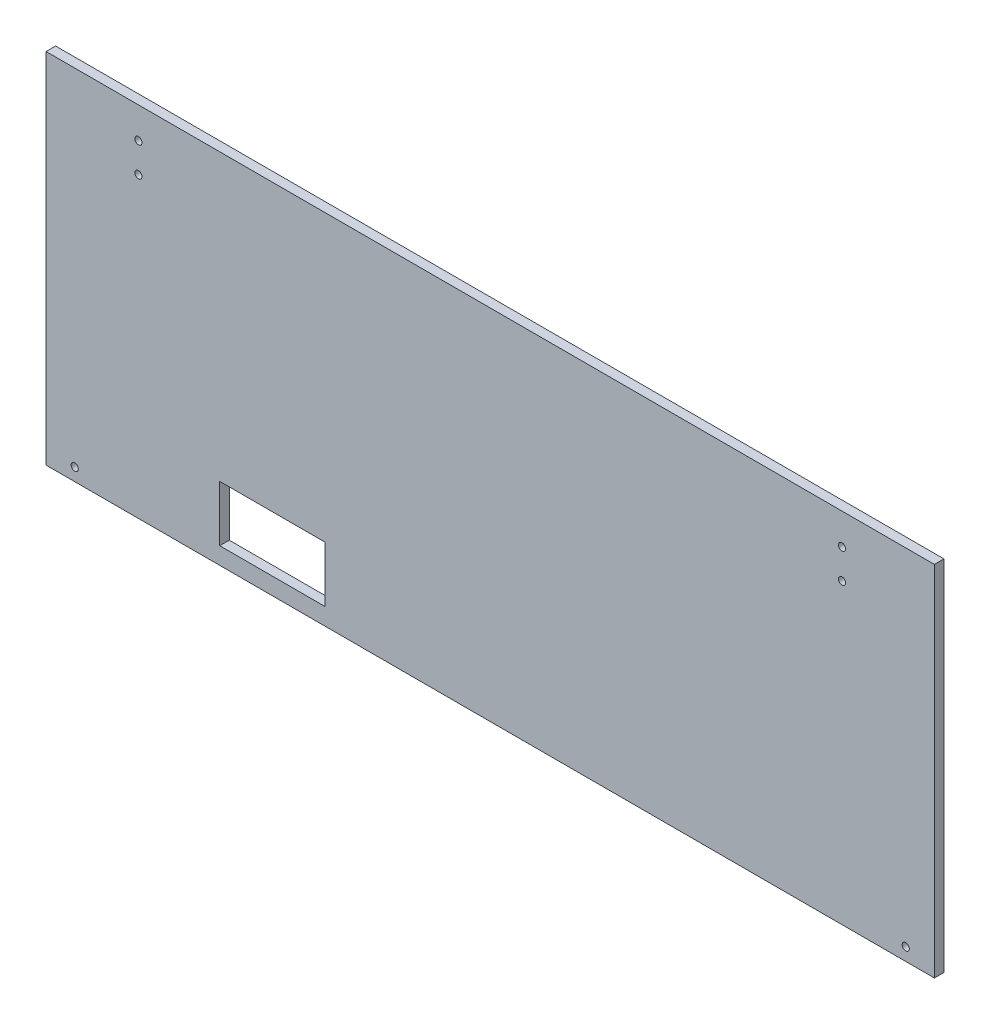
SolidWorks part; units mm, degrees
material "Pino"
ref_plane "Piano frontale" through (0, 0, 0) normal (0, 0, 1) x (1, 0, 0)
ref_plane "Piano superiore" through (0, 0, 0) normal (0, 1, 0) x (1, 0, 0)
ref_plane "Piano destro" through (0, 0, 0) normal (1, 0, 0) x (0, 0, -1)
sketch "Schizzo1" plane through (0, 0, 0) normal (0, 0, 1) x (1, 0, 0)
  line L1 (279, -112.5) -> (-279, -112.5)
  line L2 (279, -112.5) -> (279, 112.5)
  line L3 (279, 112.5) -> (-279, 112.5)
  line L4 (-279, -112.5) -> (-279, 112.5)
  line L5 (279, -112.5) -> (-279, 112.5) construction
  line L6 (279, 112.5) -> (-279, -112.5) construction
  point P4 (0, 0)
  dimension "D1" = 225
  dimension "D2" = 558
extrude "Estrusione-Estrusione1" add sketch "Schizzo1" along normal blind 6
sketch "Schizzo2" plane through (0, 0, 0) normal (0, 0, -1) x (-1, 0, 0)
  line L0 (279, -112.5) -> (-279, -112.5) construction
  line L1 (103.9257, -101.8) -> (169.9257, -101.8)
  line L2 (103.9257, -101.8) -> (103.9257, -66.8)
  line L3 (103.9257, -66.8) -> (169.9257, -66.8)
  line L4 (169.9257, -101.8) -> (169.9257, -66.8)
  line L5 (279, 112.5) -> (279, -112.5) construction
  line L6 (-279, -112.5) -> (-279, 112.5) construction
  circle A0 centre (-221, 93) radius 2.25
  circle A1 centre (-221, 74.5) radius 2.25
  circle A2 centre (221, 93) radius 2.25
  circle A3 centre (221, 74.5) radius 2.25
  circle A4 centre (-261, -104.5) radius 2.25
  circle A5 centre (261, -104.5) radius 2.25
  point P28 (-252.9189, -112.2718)
  dimension "D1" = 4.5
  dimension "D2" = 10.7
  dimension "D3" = 66
  dimension "D4" = 109.0743
  dimension "D5" = 35
  dimension "D6" = 18
  dimension "D7" = 8
  dimension "D8" = 18
  dimension "D9" = 8
extrude "Taglio-Estrusione1" cut sketch "Schizzo2" against normal blind 10
